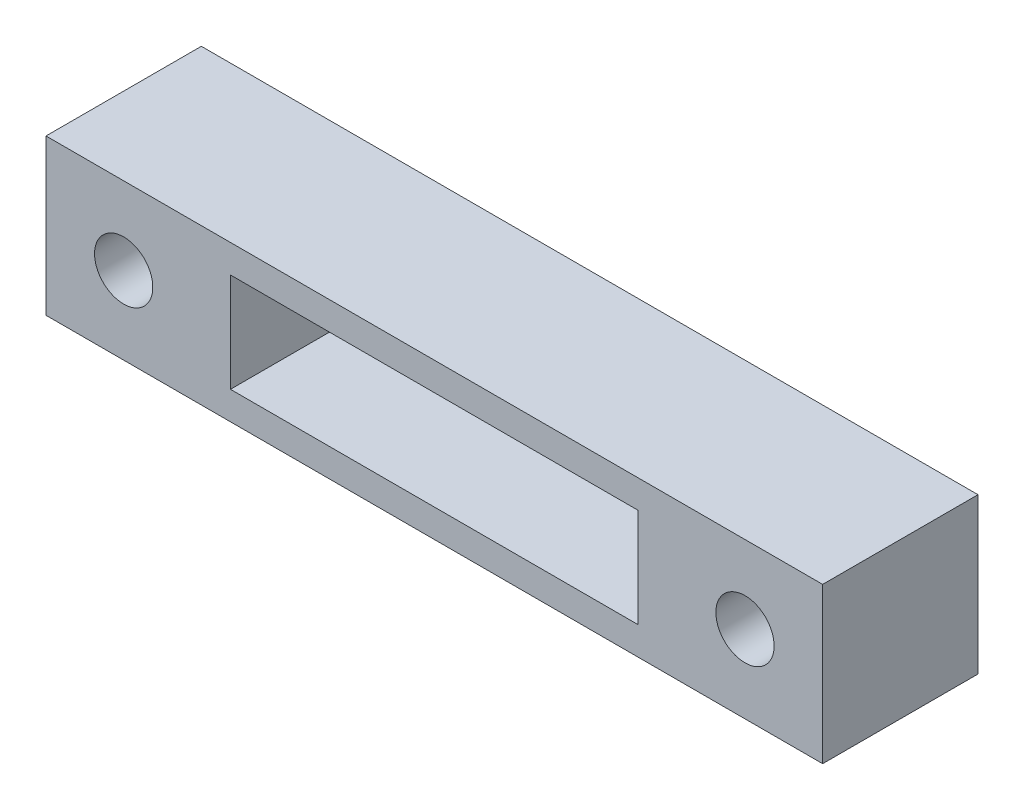
SolidWorks part; units mm, degrees
ref_plane "Front Plane" through (0, 0, 0) normal (0, 0, 1) x (1, 0, 0)
ref_plane "Top Plane" through (0, 0, 0) normal (0, 1, 0) x (1, 0, 0)
ref_plane "Right Plane" through (0, 0, 0) normal (1, 0, 0) x (0, 0, -1)
sketch "Sketch1" plane through (0, 0, 0) normal (0, 1, 0) x (1, 0, 0)
  line L1 (-20, -20) -> (20, -20)
  line L2 (-20, -20) -> (-20, 20)
  line L3 (-20, 20) -> (20, 20)
  line L4 (20, -20) -> (20, 20)
  line L5 (-20, -20) -> (20, 20) construction
  line L6 (-20, 20) -> (20, -20) construction
  line L7 (-10.5, -17.5) -> (10.5, -17.5)
  line L8 (-10.5, -17.5) -> (-10.5, 17.5)
  line L9 (-10.5, 17.5) -> (10.5, 17.5)
  line L10 (10.5, -17.5) -> (10.5, 17.5)
  line L11 (-10.5, -17.5) -> (10.5, 17.5) construction
  line L12 (-10.5, 17.5) -> (10.5, -17.5) construction
  line L13 (-20, 20) -> (20, 20)
  line L14 (-20, 20) -> (-20, 12)
  line L15 (-20, 12) -> (20, 12)
  line L16 (20, 20) -> (20, 12)
  point P0 (0, 0)
  point P6 (0, 0)
  dimension "D1" = 40
  dimension "D2" = 40
  dimension "D3" = 35
  dimension "D4" = 21
  dimension "D5" = 8
extrude "Boss-Extrude1" add sketch "Sketch1" along normal blind 8 contours L2 L15 L8 L9 L10 L4 L3 | L8 L15 L10 L9
sketch "Sketch2" plane through (0, 0, -12) normal (0, 0, 1) x (1, 0, 0)
  line L1 (0, 0) -> (0, 8)
  line L2 (-20, 0) -> (20, 0) construction
  line L3 (-20, 8) -> (20, 8) construction
  line L4 (-10.5, 1.45) -> (10.5, 1.45)
  line L5 (-10.5, 1.45) -> (-10.5, 6.55)
  line L6 (-10.5, 6.55) -> (10.5, 6.55)
  line L7 (10.5, 1.45) -> (10.5, 6.55)
  line L8 (-10.5, 1.45) -> (10.5, 6.55) construction
  line L9 (-10.5, 6.55) -> (10.5, 1.45) construction
  point P1 (0, 4)
  dimension "D1" = 5.1
  dimension "D2" = 21
extrude "Cut-Extrude1" cut sketch "Sketch2" against normal blind 5.5 contours L5 L6 L7 L4
sketch "Sketch3" plane through (0, 0, -20) normal (0, 0, -1) x (-1, 0, 0)
  circle A0 centre (-16, 4) radius 1.5
  circle A1 centre (16, 4) radius 1.5
extrude "Cut-Extrude2" cut sketch "Sketch3" against normal blind 10
